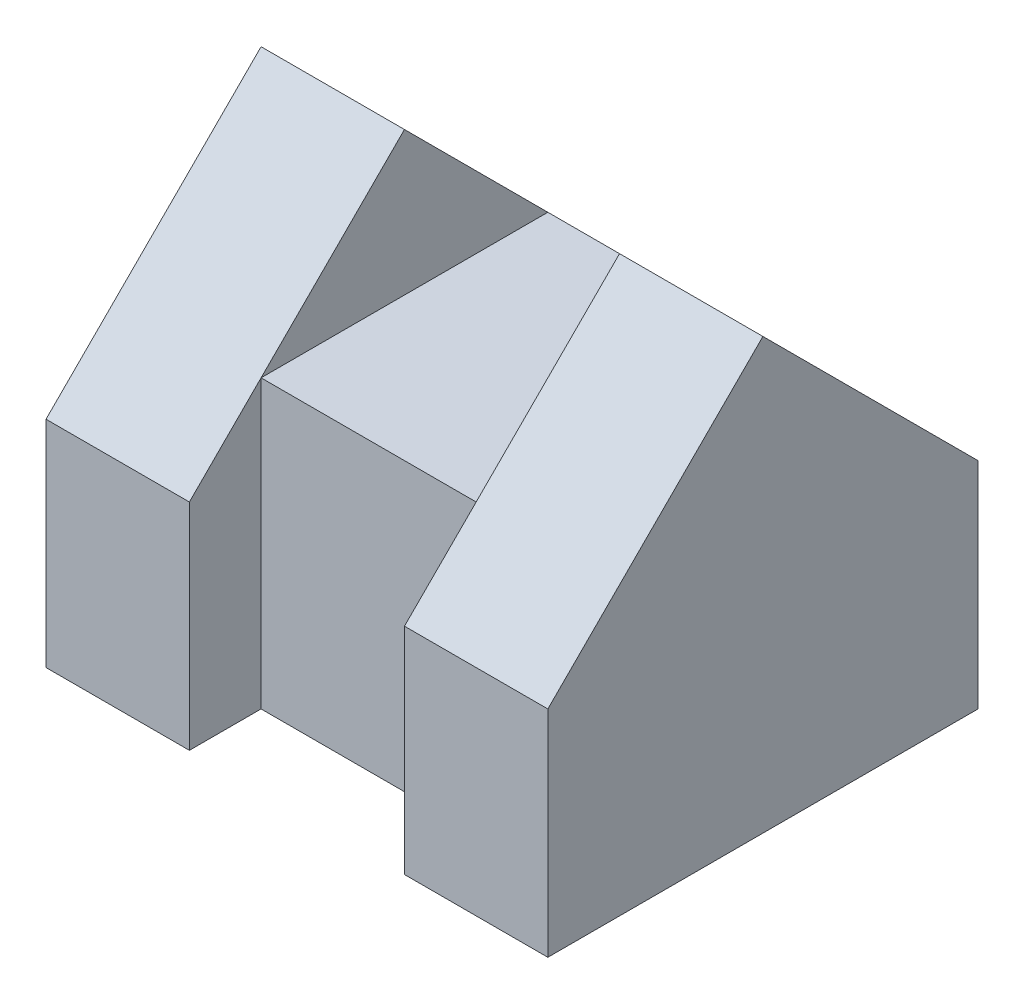
SolidWorks part; units mm, degrees
material "Ti-8Mn annealed sheet (SS)"
ref_plane "Front Plane" through (0, 0, 0) normal (0, 0, 1) x (1, 0, 0)
ref_plane "Top Plane" through (0, 0, 0) normal (0, 1, 0) x (1, 0, 0)
ref_plane "Right Plane" through (0, 0, 0) normal (1, 0, 0) x (0, 0, -1)
sketch "Sketch2" plane through (0, 0, 0) normal (0, 0, 1) x (1, 0, 0)
  line L1 (-88.9, -76.2) -> (88.9, -76.2)
  line L2 (-88.9, -76.2) -> (-88.9, 76.2)
  line L3 (-88.9, 76.2) -> (88.9, 76.2)
  line L4 (88.9, -76.2) -> (88.9, 76.2)
  line L5 (-88.9, -76.2) -> (88.9, 76.2) construction
  line L6 (-88.9, 76.2) -> (88.9, -76.2) construction
  point P0 (0, 0)
  dimension "D1" = 177.8
  dimension "D2" = 152.4
extrude "Boss-Extrude1" add sketch "Sketch2" along normal mid plane 152.4
sketch "Sketch10" plane through (0, 0, 76.2) normal (0, 0, 1) x (1, 0, 0)
  line L0 (88.9, 76.2) -> (-88.9, 76.2) construction
  line L1 (-38.1, 76.2) -> (38.1, 76.2)
  line L2 (-38.1, 76.2) -> (-38.1, 25.4)
  line L3 (-38.1, 25.4) -> (38.1, 25.4)
  line L4 (38.1, 76.2) -> (38.1, 25.4)
  line L5 (-38.1, 76.2) -> (38.1, 25.4) construction
  line L6 (-38.1, 25.4) -> (38.1, 76.2) construction
  point P4 (0, 50.8)
  dimension "D1" = 76.2
  dimension "D2" = 0
  dimension "D3" = 50.8
extrude "Cut-Extrude2" cut sketch "Sketch10" against normal through all
sketch "Sketch12" plane through (0, 25.4, 0) normal (0, 1, 0) x (1, 0, 0)
  line L0 (38.1, 76.2) -> (38.1, -76.2) construction
  line L1 (-38.1, -76.2) -> (38.1, -76.2)
  line L2 (-38.1, -76.2) -> (-38.1, -50.8)
  line L3 (-38.1, -50.8) -> (38.1, -50.8)
  line L4 (38.1, -76.2) -> (38.1, -50.8)
  line L5 (-38.1, -76.2) -> (38.1, -50.8) construction
  line L6 (-38.1, -50.8) -> (38.1, -76.2) construction
  line L7 (-38.1, 0) -> (38.1, 0) construction
  line L8 (-38.1, 76.2) -> (-38.1, -76.2) construction
  line L9 (38.1, 76.2) -> (38.1, -76.2) construction
  line L10 (-38.1, 50.8) -> (38.1, 50.8)
  line L11 (38.1, 76.2) -> (38.1, 50.8)
  line L12 (-38.1, 76.2) -> (38.1, 76.2)
  line L13 (-38.1, 76.2) -> (-38.1, 50.8)
  point P4 (0, -63.5)
  dimension "D1" = 25.4
extrude "Cut-Extrude3" cut sketch "Sketch12" against normal through all
sketch "Sketch13" plane through (88.9, 0, 0) normal (1, 0, 0) x (0, 0, -1)
  line L0 (-76.2, 0) -> (0, 76.2)
  line L1 (-76.2, -76.2) -> (-76.2, 76.2) construction
  line L2 (-76.2, 76.2) -> (76.2, 76.2) construction
  line L3 (76.2, 76.2) -> (-76.2, 76.2)
  line L4 (-76.2, 76.2) -> (-76.2, 0)
  line L5 (0, 76.2) -> (0, -76.2) construction
  line L6 (-76.2, -76.2) -> (76.2, -76.2) construction
  line L7 (76.2, 0) -> (0, 76.2)
  line L8 (76.2, 76.2) -> (76.2, 0)
  line M5 (76.2, -76.2) -> (76.2, 76.2)
  line M6 (76.2, 76.2) -> (-76.2, 76.2)
  line M7 (-76.2, 76.2) -> (-76.2, -76.2)
extrude "Cut-Extrude4" cut sketch "Sketch13" against normal through all contours L7 M5 M6 | L0 M7 M6
